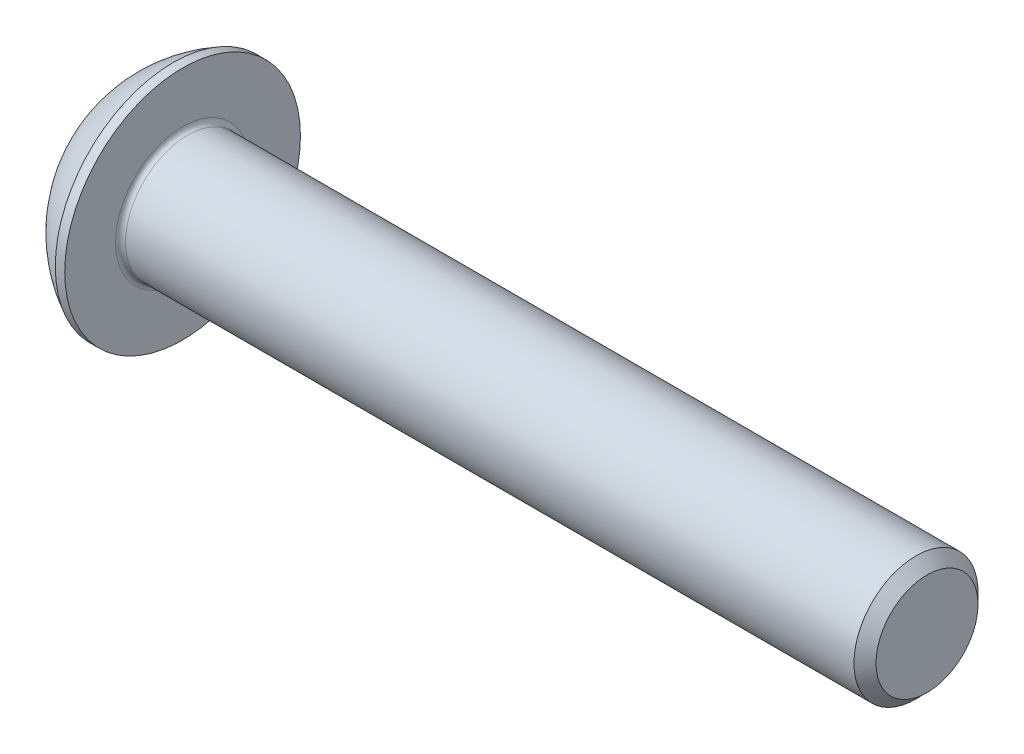
SolidWorks part; units mm, degrees
ref_plane "Plane1" through (0, 0, 0) normal (0, 0, 1) x (1, 0, 0)
ref_plane "Plane2" through (0, 0, 0) normal (0, 1, 0) x (1, 0, 0)
ref_plane "Plane3" through (0, 0, 0) normal (1, 0, 0) x (0, 0, -1)
sketch "BodySke" plane through (0, 0, 0) normal (0, 0, 1) x (1, 0, 0)
  line L0 (32.75, 0) -> (32.75, 2.055)
  line L1 (32.305, 2.5) -> (2.75, 2.5)
  line L2 (2.75, 2.5) -> (2.75, 4.75)
  line L3 (2.75, 4.75) -> (2.37, 4.75)
  line L4 (0, 0) -> (101.6, 0) construction
  line L5 (2.75, -4.75) -> (2.37, -4.75) construction
  line L6 (55.6768, -2.5) -> (2.75, -2.5) construction
  line L7 (32.75, 0) -> (0, 0)
  line L8 (0, 2.375) -> (0, -2.375) construction
  line L9 (0, 0) -> (0, 2.375)
  line L10 (32.75, 2.055) -> (32.305, 2.5)
  line L11 (32.75, -2.055) -> (32.305, -2.5) construction
  line L12 (3.55, 9.525) -> (3.55, -2.5) construction
  line L13 (2.75, 9.525) -> (2.75, -2.5) construction
  arc A1 (0, 2.375) -> (2.37, 4.75) centre (4.755, 0) cw
  dimension "Head_side_ht" = 0.38
  dimension "Body_ch_ang" = 45
revolve "BaseBody" add sketch "BodySke" angle 360 about L4
cosmetic thread "ThreadCosmetic" [suppressed] parameters "Thread_length"=28.4, "Thread_minor"=4.11
fillet "Fillet1" radius 0.2 1 edges at (2.75, 0, 2.5)
sketch "Sketch2" plane through (0, 0, 0) normal (0, 0, 1) x (1, 0, 0)
  line L0 (0, 1.5) -> (1.56, 1.5)
  line L1 (1.56, 1.5) -> (2.426, 0)
  line L3 (2.426, 0) -> (0, 0)
  line L4 (0, 0) -> (0, 1.5)
  line L5 (0, -1.5) -> (1.56, -1.5) construction
  line L6 (0, 0) -> (47.625, 0) construction
  dimension "D2" = 60
  dimension "PreBroach_depth" = 1.56
  dimension "PreBroach_dia" = 3
revolve "PreBroach" cut sketch "Sketch2" angle 360 about L6
sketch "Sketch3" plane through (0, 0, 0) normal (1, 0, 0) x (0, 0, -1)
  line L0 (-1.5, -0.866) -> (-1.5, 0.866)
  line L1 (-1.5, 0.866) -> (0, 1.7321)
  line L2 (0, 1.7321) -> (1.5, 0.866)
  line L3 (1.5, 0.866) -> (1.5, -0.866)
  line L4 (1.5, -0.866) -> (0, -1.7321)
  line L5 (0, -1.7321) -> (-1.5, -0.866)
extrude "Hex" cut sketch "Sketch3" along normal blind 1.56
sketch "ThdSchSke" plane through (0, 0, 0) normal (0, 0, 1) x (1, 0, 0)
  line L0 (4.35, -2.055) -> (4.0384, -2.5)
  line L1 (4.35, -2.055) -> (4.6616, -2.5)
  line L2 (4.6616, -2.5) -> (4.6616, -3.125)
  line L3 (-3.175, 0) -> (5.1513, 0) construction
  line L5 (4.6616, -3.125) -> (4.0384, -3.125)
  line L6 (4.0384, -3.125) -> (4.0384, -2.5)
  dimension "SideAngle" = 55
  dimension "VeeAngle" = 70
revolve "ThreadSchematic" [suppressed] cut sketch "ThdSchSke" angle 360 about L3
pattern_linear "ThdSchPat" [suppressed]
equation "\"D1@BodySke\" = \"Head_dia@BodySke\" * .5"
equation "\"Thread_minor@ThreadCosmetic\" = \"Minor_dia@BodySke\""
equation "\"D1@Sketch3\" = \"Hex_size@Sketch3\" / 2"
equation "\"D2@Sketch3\" = \"D1@Sketch3\""
equation "\"D3@Sketch3\" = \"Hex_size@Sketch3\""
equation "\"Thread_length@ThreadCosmetic\" = ((sgn( (\"Length@BodySke\" - \"Advance@BodySke\" * 2.0) - \"Thread_nom@BodySke\" )-1)*( (\"Length@BodySke\" - \"Advance@BodySke\" * 2.0) - \"Thread_nom@BodySke\" ))/-2+ \"Thread_nom@BodySke\""
equation "\"Thread_minor@ThdSchSke\" = \"Minor_dia@BodySke\""
equation "\"Diameter@ThdSchSke\" = \"Diameter@BodySke\""
equation "\"Overcut@ThdSchSke\" = \"Diameter@BodySke\" * 1.25"
equation "\"Start@ThdSchSke\" = \"Head_ht@BodySke\" + \"Length@BodySke\" - \"Thread_length@ThreadCosmetic\"  '---Non-countersunk---"
equation "\"Num_threads@ThdSchPat\" = int( \"Thread_length@ThreadCosmetic\" / \"Advance@BodySke\" + 0.999 )  + 1"
equation "\"Advance@ThdSchPat\" = \"Thread_length@ThreadCosmetic\" /  (\"Num_threads@ThdSchPat\" - 1) 'relax it"
equation "\"Num_threads@ThdSchPat\" = \"Num_threads@ThdSchPat\" - sgn( \"Num_threads@ThdSchPat\" - 1) '---chamfered tips only---"
